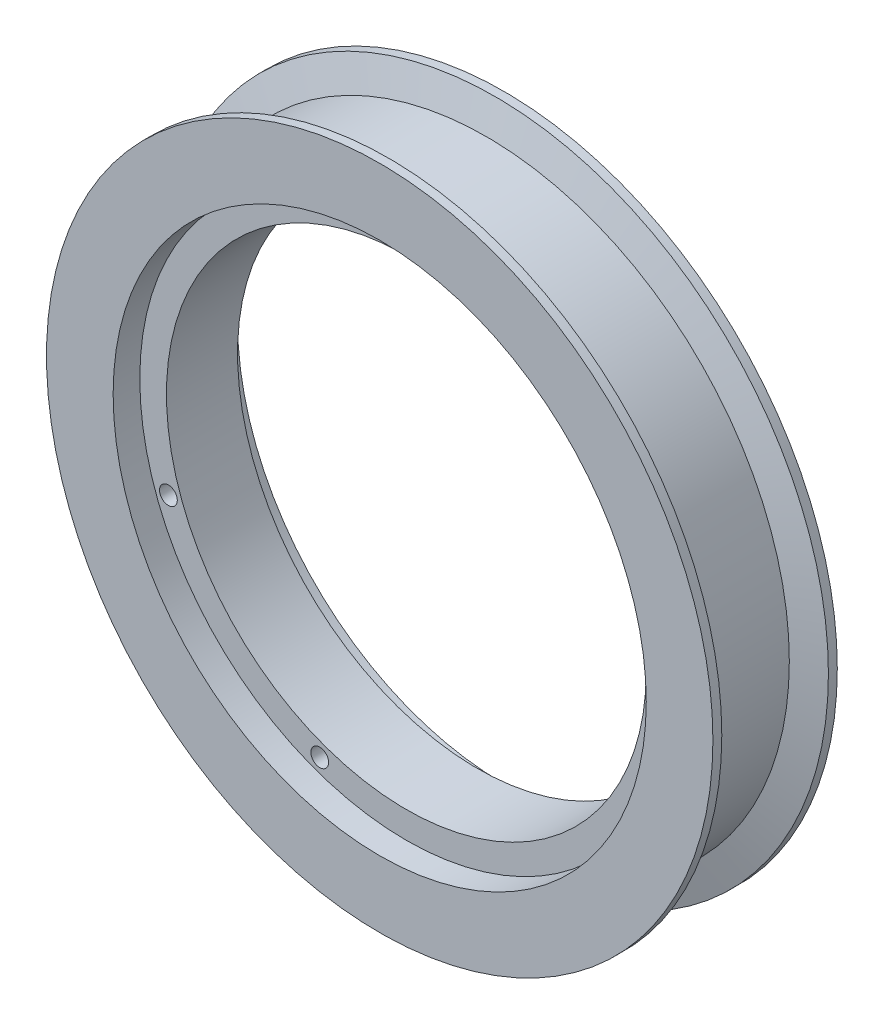
SolidWorks part; units mm, degrees
ref_plane "Front Plane" through (0, 0, 0) normal (0, 0, 1) x (1, 0, 0)
ref_plane "Top Plane" through (0, 0, 0) normal (0, 1, 0) x (1, 0, 0)
ref_plane "Right Plane" through (0, 0, 0) normal (1, 0, 0) x (0, 0, -1)
sketch "Sketch1" plane through (0, 0, 0) normal (0, 0, 1) x (1, 0, 0)
  circle A0 centre (0, 0) radius 82.55
extrude "Boss-Extrude1" add sketch "Sketch1" along normal blind 25.4
sketch "Sketch2" plane through (0, 0, 0) normal (0, 0, 1) x (1, 0, 0)
  circle A0 centre (0, 0) radius 68.58
extrude "Cut-Extrude1" cut sketch "Sketch2" along normal blind 25.4
sketch "Sketch3" plane through (0, 0, 0) normal (0, 0, 1) x (1, 0, 0)
  circle A0 centre (0, 0) radius 76.2
extrude "Cut-Extrude2" cut sketch "Sketch3" along normal blind 2.54
sketch "Sketch4" plane through (0, 0, 25.4) normal (0, 0, 1) x (1, 0, 0)
  circle A0 centre (0, 0) radius 76.2
extrude "Cut-Extrude3" cut sketch "Sketch4" against normal blind 2.54
chamfer "Chamfer5" distance 0.254 angle 45 1 edges at (82.55, 0, 0)
chamfer "Chamfer6" distance 0.254 angle 45 1 edges at (82.55, 0, 25.4)
sketch "Sketch6" plane through (0, 0, 0) normal (0, 0, 1) x (1, 0, 0)
  line L0 (0, 0) -> (0, 76.2) construction
  line L1 (0, 0) -> (68.58, 0) construction
  line L2 (0, 0) -> (51.1875, 51.1875) construction
  line L3 (0, 0) -> (-51.1875, 51.1875) construction
  circle A1 centre (0, 0) radius 76.2 construction
  circle A2 centre (0, 0) radius 68.58 construction
  circle A5 centre (68.0243, 24.7588) radius 2.54
  circle A6 centre (-68.0243, -24.7588) radius 2.54
  circle A7 centre (24.7588, 68.0243) radius 2.54
  circle A8 centre (-24.7588, -68.0243) radius 2.54
  point P24 (0, 0)
  point P29 (0, 0)
extrude "Cut-Extrude4" cut sketch "Sketch6" along normal through all
sketch "Sketch7" plane through (0, 0, 0) normal (0, 0, -1) x (-1, 0, 0)
  circle A0 centre (0, 0) radius 76.2
  circle A1 centre (0, 0) radius 95.25
extrude "Boss-Extrude2" add sketch "Sketch7" against normal blind 25.4
sketch "Sketch9" plane through (0, 0, 25.4) normal (0, 0, 1) x (1, 0, 0)
  circle A0 centre (0, 0) radius 76.2
  circle A1 centre (0, 0) radius 95.25
extrude "Boss-Extrude3" add sketch "Sketch9" along normal blind 5.08
ref_plane "Plane1" through (0, 0, 12.7) normal (0, 0, -1) x (-1, 0, 0)
mirror "Mirror1" about plane through (0, 0, 12.7) normal (0, 0, -1) of "Boss-Extrude3"
sketch "Sketch10" plane through (0, 0, 0) normal (1, 0, 0) x (0, 0, -1)
  line L0 (-12.7, 95.25) -> (-12.7, -95.25) construction
  line L1 (5.08, 95.25) -> (-30.48, 95.25) construction
  line L2 (-30.48, -95.25) -> (5.08, -95.25) construction
  line L3 (-12.7, 95.25) -> (-12.7, 86.614) construction
  line L4 (0, 86.614) -> (-25.4, 86.614)
  line L5 (2.54, 95.25) -> (-27.94, 95.25)
  line L6 (-27.94, 95.25) -> (-25.4, 86.614)
  line L7 (2.54, 95.25) -> (0, 86.614)
ref_axis "Axis1" through (0, 0, 22.86) along (0, 0, -1)
revolve "Cut-Revolve1" cut sketch "Sketch10" angle 360 about axis through (0, 0, 22.86) along (0, 0, -1)
